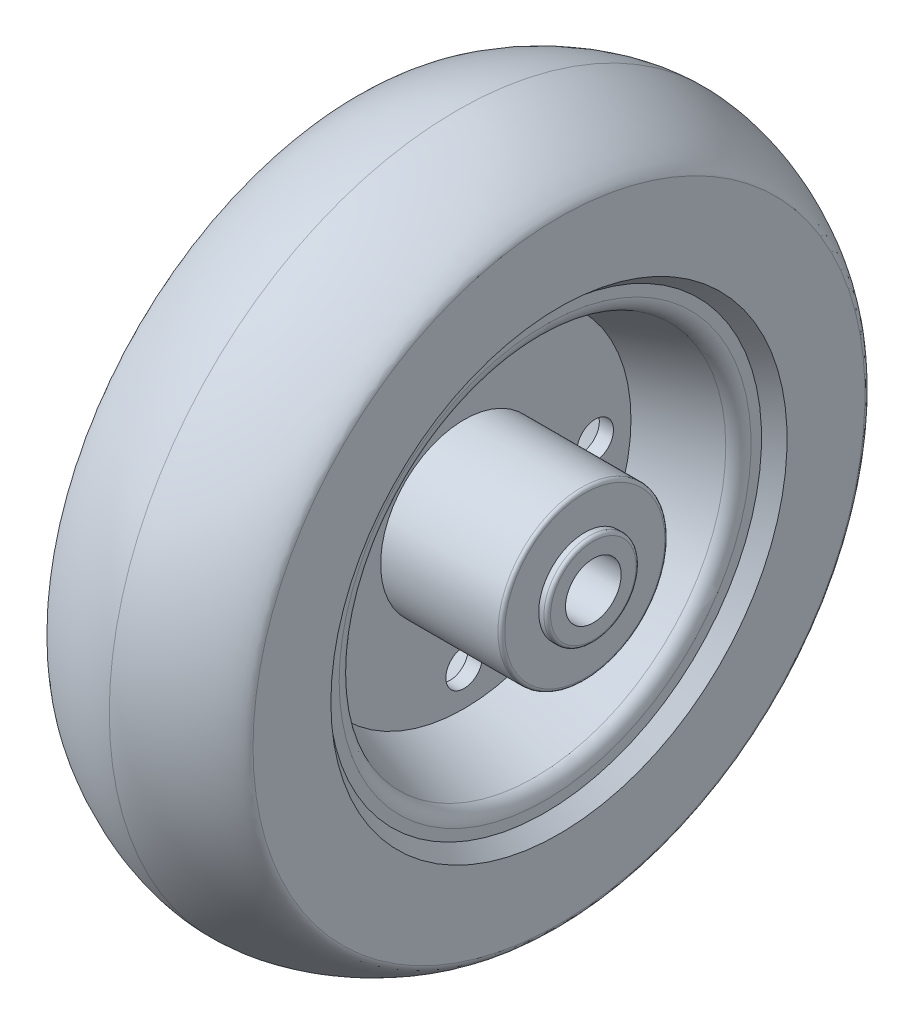
SolidWorks part; units mm, degrees
ref_plane "Front Plane" through (0, 0, 0) normal (0, 0, 1) x (1, 0, 0)
ref_plane "Top Plane" through (0, 0, 0) normal (0, 1, 0) x (1, 0, 0)
ref_plane "Right Plane" through (0, 0, 0) normal (1, 0, 0) x (0, 0, -1)
sketch "Sketch5" plane through (0, 0, 0) normal (0, 0, 1) x (1, 0, 0)
  line L0 (-23.2791, 0) -> (-23.2791, 69.85)
  line L1 (0, -1000) -> (0, 49000) construction
  line L2 (-23.2791, 0) -> (23.2791, 0) construction
  line L3 (23.2791, 0) -> (23.2791, 69.85)
  line L4 (-23.2791, 73.6345) -> (-23.2791, 66.0655) construction
  line L5 (2.3783, 79.375) -> (-2.3783, 79.375) construction
  line L6 (-23.2791, 0) -> (23.2791, 0)
  spline S0 degree 3 poles (-23.2791, 69.85) (-23.2791, 72.068) (-10.5362, 79.375) (0, 79.375) knots 0 0 0 0 1 1 1 1
  spline S1 degree 3 poles (23.2791, 69.85) (23.2791, 72.068) (10.5362, 79.375) (0, 79.375) knots 0 0 0 0 1 1 1 1
  point P8 (0, 0)
  dimension "D1" = 79.375
  dimension "D2" = 69.85
  dimension "D3" = 46.5582
revolve "Revolve1" add sketch "Sketch5" angle 360 about L6
sketch "Sketch7" plane through (0, 0, 0) normal (0, 1, 0) x (1, 0, 0)
  line L0 (-1000, 0) -> (49000, 0) construction
  line L1 (1.6129, 0) -> (1.6129, 38.1)
  line L2 (1.6129, 38.1) -> (17.7065, 43.645)
  line L3 (20.1041, 47.007) -> (20.1041, 49.4128)
  line L4 (20.1041, 49.4128) -> (23.2791, 52.07)
  line L5 (23.2791, -69.85) -> (23.2791, 69.85) construction
  line L6 (23.2791, 52.07) -> (23.2791, 0)
  line L7 (1.6129, 0) -> (23.2791, 0)
  line L8 (0, -79.375) -> (0, 79.375) construction
  arc A0 (17.7065, 43.645) -> (20.1041, 47.007) centre (16.5481, 47.007) ccw
  point P12 (20.1041, 44.4711)
  dimension "D3" = 19.558
  dimension "D7" = 3.556
  dimension "D1" = 52.07
  dimension "D2" = 4.1402
  dimension "D4" = 38.1
  dimension "D5" = 1.6129
  dimension "D6" = 3.175
revolve "Cut-Revolve2" cut sketch "Sketch7" angle 360 about L0
mirror "Mirror1" about plane through (0, 0, 0) normal (1, 0, 0) of "Cut-Revolve2"
sketch "Sketch8" plane through (1.6129, 0, 0) normal (1, 0, 0) x (0, 0, -1)
  circle A1 centre (0, 0) radius 19.05
  dimension "D1" = 38.1
extrude "Boss-Extrude1" add sketch "Sketch8" along normal blind 27.5463
sketch "Sketch9" plane through (29.1592, 0, 0) normal (1, 0, 0) x (0, 0, -1)
  circle A0 centre (0, 0) radius 10.5156
  dimension "D1" = 21.0312
extrude "Boss-Extrude2" add sketch "Sketch9" along normal blind 1.9558
fillet "Fillet4" radius 0.762 2 edges at (31.115, 0, -10.5156) (29.1592, 0, -19.05)
mirror "Mirror2" about plane through (0, 0, 0) normal (1, 0, 0) of "Fillet4", "Boss-Extrude2", "Boss-Extrude1"
sketch "Sketch10" plane through (-31.115, 0, 0) normal (-1, 0, 0) x (0, 0, 1)
  circle A0 centre (0, 0) radius 6.35
  dimension "D1" = 12.7
extrude "Cut-Extrude5" cut sketch "Sketch10" against normal through all
sketch "Sketch11" plane through (1.6129, 0, 0) normal (1, 0, 0) x (0, 0, -1)
  circle A0 centre (0, 29.9339) radius 4.1656
  circle A2 centre (29.9339, 0) radius 4.1656
  circle A3 centre (0, -29.9339) radius 4.1656
  circle A4 centre (-29.9339, 0) radius 4.1656
  dimension "D2" = 8.3312
  dimension "D1" = 25.7683
  dimension "D3" = 4
extrude "Cut-Extrude6" cut sketch "Sketch11" against normal through all
